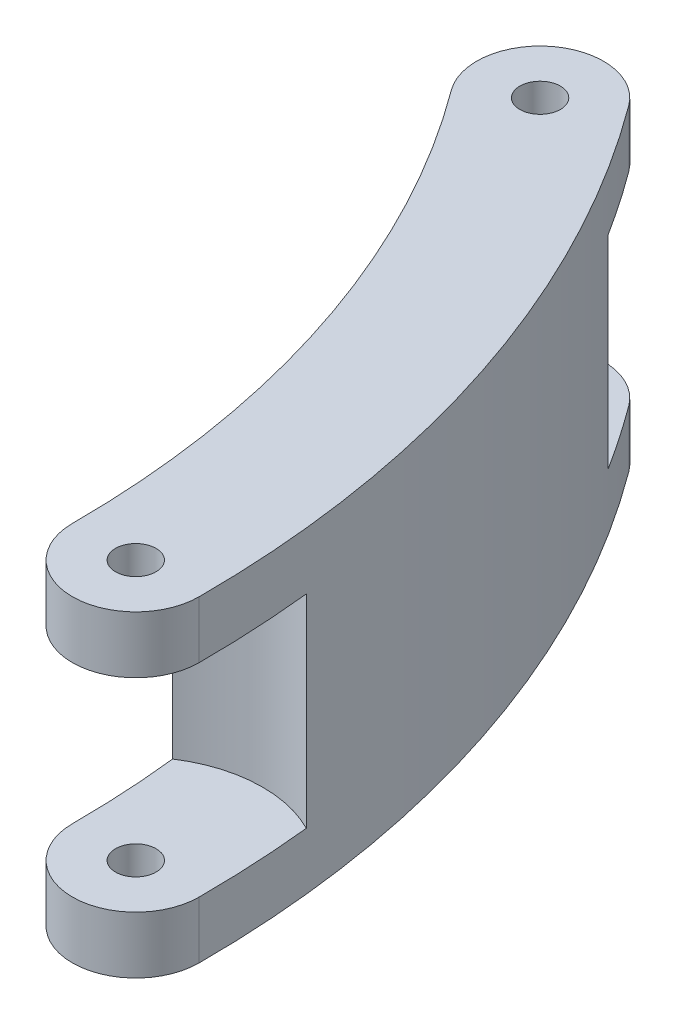
SolidWorks part; units mm, degrees
ref_plane "Front Plane" through (0, 0, 0) normal (0, 0, 1) x (1, 0, 0)
ref_plane "Top Plane" through (0, 0, 0) normal (0, 1, 0) x (1, 0, 0)
ref_plane "Right Plane" through (0, 0, 0) normal (1, 0, 0) x (0, 0, -1)
other "Configuration Table"
sketch "草图1" plane through (0, 0, 0) normal (0, 1, 0) x (1, 0, 0)
  arc A0 (60.3516, 44.5274) -> (75, 0) centre (0, 0) cw
  arc A1 (68.3984, 50.4644) -> (85, 0) centre (0, 0) cw
  arc A3 (68.3984, 50.4644) -> (60.3516, 44.5274) centre (64.375, 47.4959) ccw
  arc A4 (75, 0) -> (85, 0) centre (80, 0) ccw
  dimension "D1" = 75
  dimension "D2" = 85
  dimension "D4" = 10
  dimension "D5" = 10
  dimension "D6" = 50
extrude "凸台-拉伸1" add sketch "草图1" along normal mid plane 25
sketch "草图2" plane through (0, 0, 0) normal (0, 1, 0) x (1, 0, 0)
  line L2 (73.4206, 38.2446) -> (66.8085, 34.0827)
  line L3 (71.936, 45.2793) -> (73.4206, 38.2446)
  circle A1 centre (80, 0) radius 10
  arc A2 (68.3984, 50.4644) -> (60.3516, 44.5274) centre (64.375, 47.4959) ccw construction
  arc A3 (68.3984, 50.4644) -> (60.3516, 44.5274) centre (64.375, 47.4959) ccw
  arc A8 (66.8085, 34.0827) -> (60.3516, 44.5274) centre (0, 0) ccw
  arc A9 (71.936, 45.2793) -> (68.3984, 50.4644) centre (0, 0) ccw
  dimension "D1" = 20
extrude "切除-拉伸1" cut sketch "草图2" against normal mid plane 16
sketch "草图3" plane through (0, 12.5, 0) normal (0, 1, 0) x (1, 0, 0)
  circle A0 centre (64.375, 47.4959) radius 1.6
  circle A1 centre (80, 0) radius 1.6
  dimension "D1" = 3.2
  dimension "D2" = 3.2
extrude "切除-拉伸2" cut sketch "草图3" against normal through all both and the other way through all
